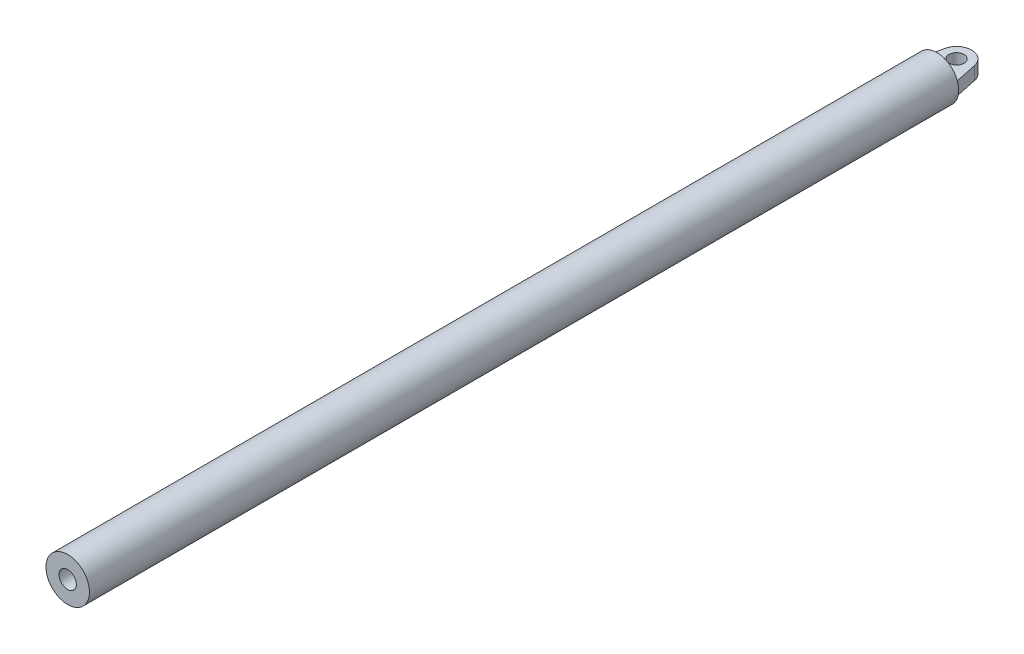
SolidWorks part; units mm, degrees
ref_plane "Front Plane" through (0, 0, 0) normal (0, 0, 1) x (1, 0, 0)
ref_plane "Top Plane" through (0, 0, 0) normal (0, 1, 0) x (1, 0, 0)
ref_plane "Right Plane" through (0, 0, 0) normal (1, 0, 0) x (0, 0, -1)
sketch "Sketch1" plane through (0, 0, 0) normal (0, 0, 1) x (1, 0, 0)
  circle A0 centre (0, 0) radius 50
  dimension "D1" = 100
extrude "Boss-Extrude1" add sketch "Sketch1" along normal blind 2000
shell "Shell1" thickness 30
sketch "Sketch2" plane through (0, 0, 0) normal (0, 1, 0) x (1, 0, 0)
  line L0 (-45, 0) -> (-34.2808, 52.0586)
  line L1 (50, 0) -> (-50, 0) construction
  line L2 (0, 0) -> (0, 231.1371) construction
  line L3 (34.2808, 52.0586) -> (45, 0)
  line L4 (-45, 0) -> (45, 0)
  circle A0 centre (0, 45) radius 17.5
  arc A1 (-34.2808, 52.0586) -> (34.2808, 52.0586) centre (0, 45) cw
  dimension "D1" = 35
  dimension "D2" = 35
  dimension "D3" = 45
  dimension "D4" = 45
extrude "Boss-Extrude2" add sketch "Sketch2" along normal mid plane 30 contours L4 L2 A0 A1 L0 | L2 L4 L3 A1 A0
